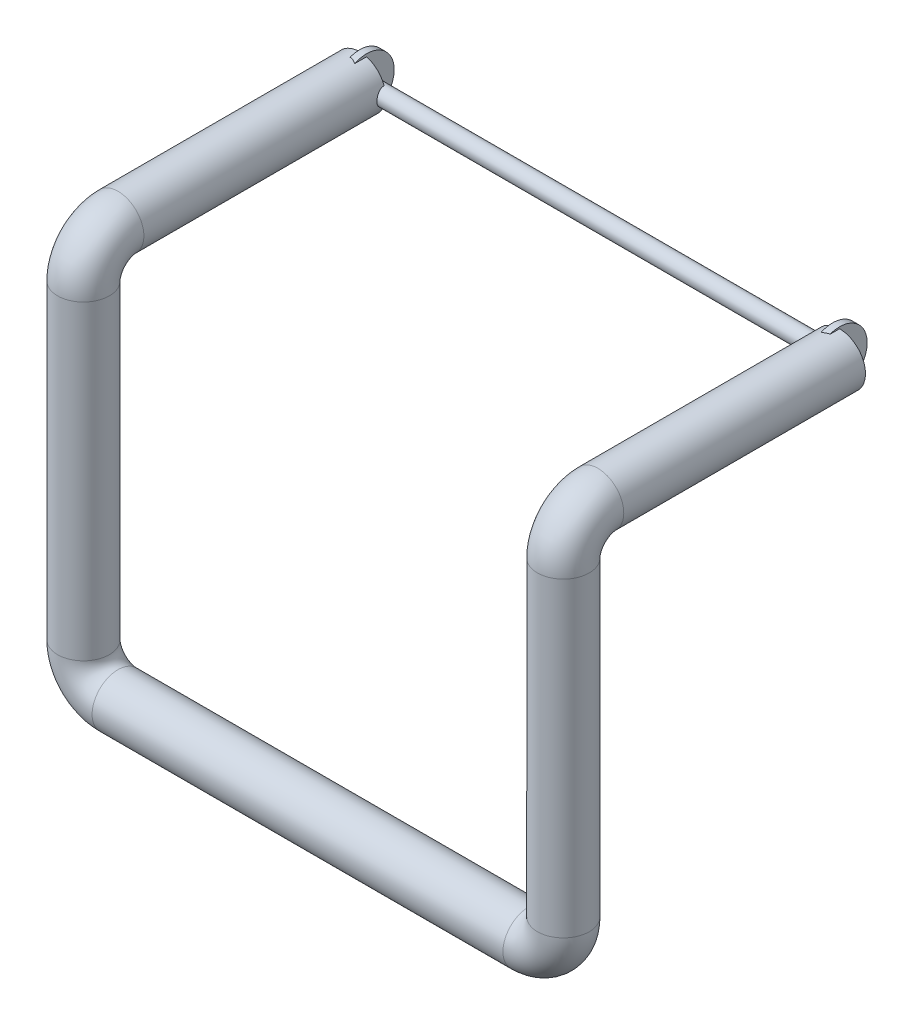
SolidWorks part; units mm, degrees
material "Nylon 6/10"
ref_plane "Front Plane" through (0, 0, 0) normal (0, 0, 1) x (1, 0, 0)
ref_plane "Top Plane" through (0, 0, 0) normal (0, 1, 0) x (1, 0, 0)
ref_plane "Right Plane" through (0, 0, 0) normal (1, 0, 0) x (0, 0, -1)
sketch "Sketch1" plane through (0, 0, 0) normal (1, 0, 0) x (0, 0, -1)
  circle A0 centre (0, 0) radius 12.5
  dimension "D1" = 25
extrude "Boss-Extrude1" add sketch "Sketch1" along normal mid plane 675
sketch "Sketch2" plane through (337.5, 0, 0) normal (1, 0, 0) x (0, 0, -1)
  circle A0 centre (0, 0) radius 40
  dimension "D1" = 80
extrude "Boss-Extrude2" add sketch "Sketch2" along normal blind 10
ref_plane "Plane1" through (342.5, 0, 0) normal (1, 0, 0) x (0, 0, -1)
sketch3d "3DSketch4"
  line L0 (347.5, 0, 0) -> (347.5, 0, 350)
  line L1 (347.5, 0, 0) -> (337.5, 0, 0) construction
  line L2 (347.5, -50, 400) -> (347.5, -500, 400)
  line L3 (297.5, -550, 400) -> (-2.5, -550, 400)
  arc A0 (347.5, 0, 350) -> (347.5, -50, 400) centre (347.5, -50, 350) ccw
  arc A1 (347.5, -500, 400) -> (297.5, -550, 400) centre (297.5, -500, 400) ccw
  point P8 (347.5, 0, 400)
  point P9 (397.5, -50, 350)
  point P12 (347.5, -550, 400)
  point P13 (297.5, -500, 350)
  point P14 (40.7273, -298.3482, 370)
  dimension "D1" = 50
  dimension "D2" = 50
  dimension "D3" = 350
  dimension "D4" = 350
  dimension "D5" = 450
sketch "Sketch3" plane through (0, 0, 0) normal (0, 0, 1) x (1, 0, 0)
  circle A0 centre (347.5, 0) radius 37.5
  circle A1 centre (347.5, 0) radius 29.3723
  dimension "D1" = 75
sweep "Sweep1" add profiles "Sketch3" path "3DSketch4"
mirror "Mirror1" about plane through (0, 0, 0) normal (1, 0, 0) of "Sweep1", "Boss-Extrude2"
ref_plane "Plane2" through (0, -500, 0) normal (0, 1, 0) x (1, 0, 0)
